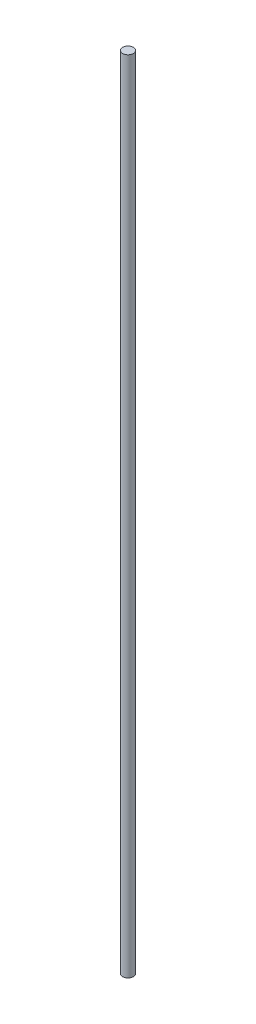
SolidWorks part; units mm, degrees
ref_plane "Plan de face" through (0, 0, 0) normal (0, 0, 1) x (1, 0, 0)
ref_plane "Plan de dessus" through (0, 0, 0) normal (0, 1, 0) x (1, 0, 0)
ref_plane "Plan de droite" through (0, 0, 0) normal (1, 0, 0) x (0, 0, -1)
sketch "Esquisse1" plane through (0, 0, 0) normal (0, 1, 0) x (1, 0, 0)
  circle A0 centre (0, 0) radius 8.75
  dimension "D1" = 17.5
extrude "Boss.-Extru.1" add sketch "Esquisse1" along normal blind 1300
